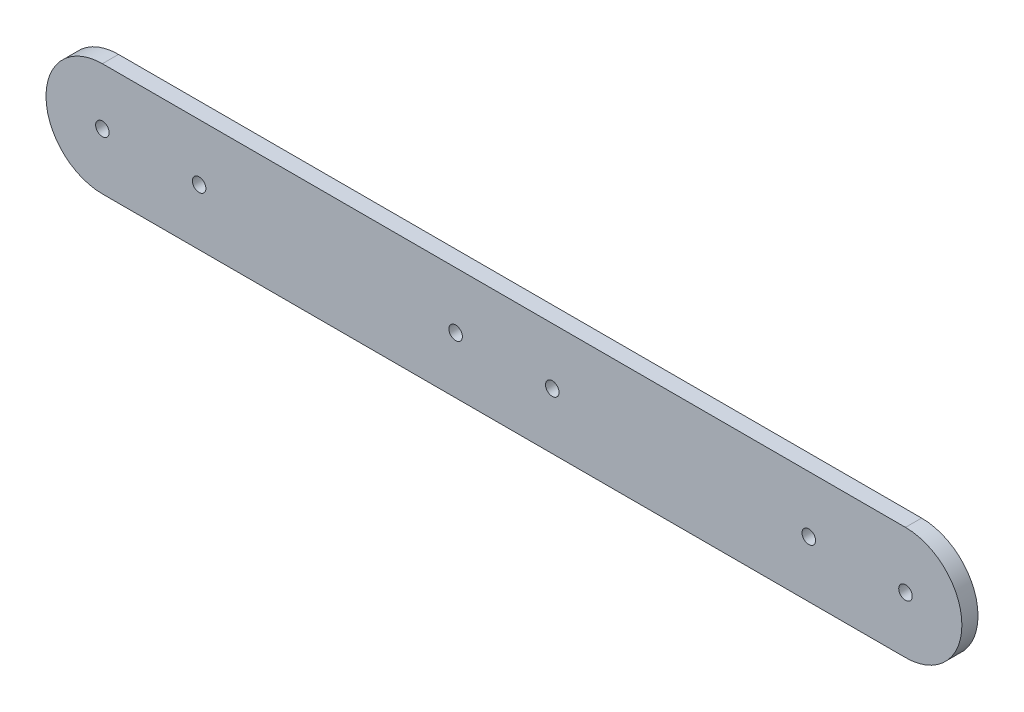
SolidWorks part; units mm, degrees
ref_plane "Front Plane" through (0, 0, 0) normal (0, 0, 1) x (1, 0, 0)
ref_plane "Top Plane" through (0, 0, 0) normal (0, 1, 0) x (1, 0, 0)
ref_plane "Right Plane" through (0, 0, 0) normal (1, 0, 0) x (0, 0, -1)
sketch "Sketch1" plane through (0, 0, 0) normal (0, 0, 1) x (1, 0, 0)
  line L0 (51.6289, 81.7) -> (300.8169, 81.7) construction
  line L5 (51.6289, 99.2) -> (300.8169, 99.2)
  line L6 (51.6289, 64.2) -> (300.8169, 64.2)
  arc A4 (51.6289, 99.2) -> (51.6289, 64.2) centre (51.6289, 81.7) ccw
  arc A5 (300.8169, 64.2) -> (300.8169, 99.2) centre (300.8169, 81.7) ccw
  circle A12 centre (300.8169, 81.7) radius 2.1
  circle A13 centre (270.8169, 81.7) radius 2.1
  circle A14 centre (191.2229, 81.7) radius 2.1
  circle A15 centre (51.6289, 81.7) radius 2.1
  circle A16 centre (81.6289, 81.7) radius 2.1
  circle A17 centre (161.2229, 81.7) radius 2.1
  point P2 (176.2229, 81.7)
  point P7 (0, 0)
  point P8 (0, 0)
  dimension "D1" = 35
extrude "Boss-Extrude1" add sketch "Sketch1" along normal blind 5
